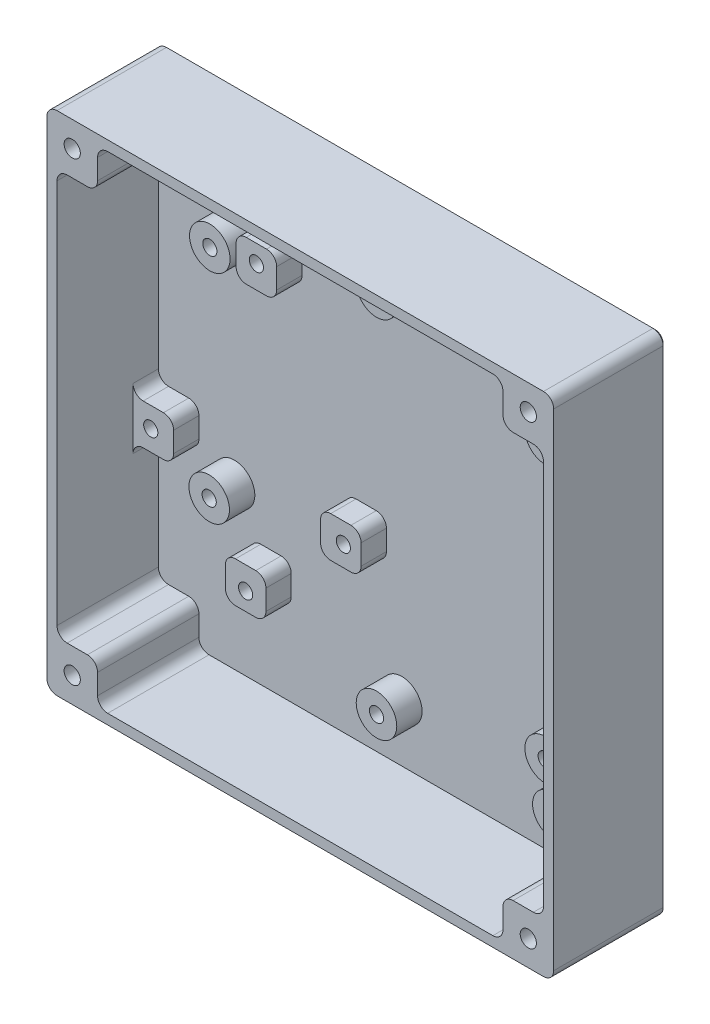
SolidWorks part; units mm, degrees
ref_plane "前视基准面" through (0, 0, 0) normal (0, 0, 1) x (1, 0, 0)
ref_plane "上视基准面" through (0, 0, 0) normal (0, 1, 0) x (1, 0, 0)
ref_plane "右视基准面" through (0, 0, 0) normal (1, 0, 0) x (0, 0, -1)
sketch "草图1" plane through (0, 0, 0) normal (0, 0, 1) x (1, 0, 0)
  line L1 (0, 0) -> (100, 0)
  line L2 (0, 0) -> (0, 100)
  line L3 (0, 100) -> (100, 100)
  line L4 (100, 0) -> (100, 100)
  dimension "D1" = 100
  dimension "D2" = 100
extrude "凸台-拉伸1" add sketch "草图1" along normal blind 2
sketch "草图2" plane through (0, 0, 2) normal (0, 0, 1) x (1, 0, 0)
  line L4 (98, 98) -> (2, 98)
  line L5 (2, 98) -> (2, 2)
  line L6 (2, 2) -> (98, 2)
  line L7 (98, 2) -> (98, 98)
  line L8 (0, 100) -> (0, 0)
  line L9 (0, 0) -> (100, 0)
  line L10 (100, 0) -> (100, 100)
  line L11 (100, 100) -> (0, 100)
  line L12 (0, 100) -> (0, 0)
  line L13 (0, 0) -> (100, 0)
  line L14 (100, 0) -> (100, 100)
  line L15 (100, 100) -> (0, 100)
  dimension "D1" = 0
  dimension "D2" = 2
extrude "凸台-拉伸2" add sketch "草图2" along normal blind 20
sketch "草图3" plane through (0, 0, 22) normal (0, 0, 1) x (1, 0, 0)
  line L0 (98, 98) -> (2, 98) construction
  line L1 (90, 98) -> (98, 98)
  line L2 (90, 98) -> (90, 90)
  line L3 (90, 90) -> (98, 90)
  line L4 (98, 98) -> (98, 90)
  line L5 (98, 2) -> (98, 98) construction
  line L7 (2, 98) -> (10, 98)
  line L8 (2, 98) -> (2, 90)
  line L9 (2, 90) -> (10, 90)
  line L10 (10, 98) -> (10, 90)
  line L11 (2, 2) -> (10, 2)
  line L12 (2, 2) -> (2, 10)
  line L13 (2, 10) -> (10, 10)
  line L14 (10, 2) -> (10, 10)
  line L15 (98, 2) -> (90, 2)
  line L16 (98, 2) -> (98, 10)
  line L17 (98, 10) -> (90, 10)
  line L18 (90, 2) -> (90, 10)
  dimension "D1" = 8
  dimension "D2" = 8
  dimension "D3" = 8
  dimension "D4" = 8
  dimension "D5" = 8
  dimension "D6" = 8
  dimension "D7" = 8
  dimension "D8" = 8
extrude "凸台-拉伸3" add sketch "草图3" against normal up to surface (20 mm away) up to face at (50, 50, 2)
sketch "草图4" plane through (0, 0, 22) normal (0, 0, 1) x (1, 0, 0)
  line L0 (100, 100) -> (0, 100) construction
  line L1 (0, 100) -> (0, 0) construction
  circle A0 centre (5, 95) radius 1.6
  circle A1 centre (95, 95) radius 1.6
  circle A2 centre (95, 5) radius 1.6
  circle A3 centre (5, 5) radius 1.6
  dimension "D1" = 3.2
  dimension "D2" = 5
  dimension "D3" = 5
  dimension "D4" = 2
  dimension "D5" = 2
extrude "切除-拉伸1" cut sketch "草图4" against normal through all
sketch "草图5" plane through (0, 0, 0) normal (0, 0, -1) x (-1, 0, 0)
  circle A0 centre (-95, 5) radius 3.05
  circle A1 centre (-5, 5) radius 3.05
  circle A2 centre (-5, 95) radius 3.05
  circle A3 centre (-95, 95) radius 3.05
  dimension "D1" = 6.1
  dimension "D2" = 2
  dimension "D3" = 2
extrude "切除-拉伸2" cut sketch "草图5" against normal blind 15
sketch "草图6" plane through (0, 0, 2) normal (0, 0, 1) x (1, 0, 0)
  circle A0 centre (50.0396, 85.2027) radius 4
  circle A1 centre (84.7107, 85.7107) radius 4
  circle A2 centre (84.8377, 13.4475) radius 4
  circle A3 centre (50.0396, 13.3205) radius 4
  dimension "D1" = 8
  dimension "D2" = 8
  dimension "D3" = 8
  dimension "D4" = 8
extrude "凸台-拉伸4" add sketch "草图6" along normal blind 5
sketch "草图7" plane through (0, 0, 7) normal (0, 0, 1) x (1, 0, 0)
  circle A0 centre (50.0396, 85.2027) radius 1.4
  circle A1 centre (84.7107, 85.7107) radius 1.4
  circle A2 centre (84.8377, 13.4475) radius 1.4
  circle A3 centre (50.0396, 13.3205) radius 1.4
  dimension "D1" = 2.8
  dimension "D2" = 2.8
  dimension "D3" = 2.8
  dimension "D4" = 2.8
extrude "切除-拉伸3" cut sketch "草图7" against normal blind 6
sketch "草图8" plane through (0, 0, 2) normal (0, 0, 1) x (1, 0, 0)
  circle A0 centre (17.1546, 76.6947) radius 4
  circle A1 centre (83.3217, 76.6947) radius 4
  circle A2 centre (83.3217, 22.2116) radius 4
  circle A3 centre (17.0276, 33.7686) radius 4
  dimension "D1" = 8
  dimension "D2" = 8
  dimension "D3" = 8
  dimension "D4" = 8
extrude "凸台-拉伸5" add sketch "草图8" along normal blind 5
sketch "草图9" plane through (0, 0, 7) normal (0, 0, 1) x (1, 0, 0)
  circle A0 centre (17.1546, 76.6947) radius 1.4
  circle A1 centre (83.3217, 76.6947) radius 1.4
  circle A2 centre (83.3217, 22.2116) radius 1.4
  circle A3 centre (17.0276, 33.7686) radius 1.4
  dimension "D1" = 2.8
  dimension "D2" = 2.8
  dimension "D3" = 2.8
  dimension "D4" = 2.8
extrude "切除-拉伸4" cut sketch "草图9" against normal blind 6
sketch "草图10" plane through (0, 0, 2) normal (0, 0, 1) x (1, 0, 0)
  line L0 (7, 77) -> (42, 77) construction
  line L1 (22.3409, 82) -> (30.3409, 82)
  line L2 (22.3409, 82) -> (22.3409, 74)
  line L3 (22.3409, 74) -> (30.3409, 74)
  line L4 (30.3409, 82) -> (30.3409, 74)
  line L5 (39, 43.1287) -> (47, 43.1287)
  line L6 (39, 43.1287) -> (39, 35.1287)
  line L7 (39, 35.1287) -> (47, 35.1287)
  line L8 (47, 43.1287) -> (47, 35.1287)
  line L9 (20.2165, 26) -> (28.2165, 26)
  line L10 (20.2165, 26) -> (20.2165, 18)
  line L11 (20.2165, 18) -> (28.2165, 18)
  line L12 (28.2165, 26) -> (28.2165, 18)
  line L13 (10, 43.8717) -> (2, 43.8717)
  line L14 (10, 43.8717) -> (10, 35.8717)
  line L15 (10, 35.8717) -> (2, 35.8717)
  line L16 (2, 43.8717) -> (2, 35.8717)
  line L17 (7, 23) -> (7, 46.8587) construction
  line L18 (7, 23) -> (42, 23) construction
  line L19 (42, 23) -> (42, 47.0044) construction
  dimension "D1" = 8
  dimension "D2" = 8
  dimension "D3" = 3
  dimension "D4" = 8
  dimension "D5" = 8
  dimension "D6" = 3
  dimension "D7" = 8
  dimension "D8" = 8
  dimension "D9" = 3
  dimension "D10" = 8
  dimension "D11" = 8
  dimension "D12" = 3
extrude "凸台-拉伸6" add sketch "草图10" along normal blind 5
sketch "草图11" plane through (0, 0, 7) normal (0, 0, 1) x (1, 0, 0)
  line L0 (7, 23) -> (7, 46.8587) construction
  line L1 (42, 23) -> (42, 47.0044) construction
  line L2 (7, 23) -> (42, 23) construction
  line L3 (7, 77) -> (42, 77) construction
  circle A0 centre (26.3409, 78.5) radius 1.4
  circle A1 centre (43.5, 39.1287) radius 1.4
  circle A2 centre (5.5, 39.8717) radius 1.4
  circle A3 centre (24.2165, 21.5) radius 1.4
  dimension "D1" = 2.8
  dimension "D2" = 1.5
  dimension "D3" = 2.8
  dimension "D4" = 1.5
  dimension "D5" = 2.8
  dimension "D6" = 1.5
  dimension "D7" = 2.8
  dimension "D8" = 1.5
extrude "切除-拉伸5" cut sketch "草图11" against normal blind 5
fillet "圆角1" radius 2 4 edges at (100, 100, 11) (100, 0, 11) (0, 100, 11) (0, 0, 11)
fillet "圆角2" radius 2 28 edges at (22.3409, 74, 4.5) (30.3409, 74, 4.5) (30.3409, 82, 4.5) (22.3409, 82, 4.5) (20.2165, 18, 4.5) (28.2165, 18, 4.5) (28.2165, 26, 4.5) (20.2165, 26, 4.5) (39, 35.1287, 4.5) (47, 43.1287, 4.5) (39, 43.1287, 4.5) (47, 35.1287, 4.5) (2, 43.8717, 4.5) (2, 90, 12) (10, 98, 12) (90, 98, 12) (90, 90, 12) (98, 90, 12) (98, 10, 12) (90, 10, 12) (90, 2, 12) (10, 2, 12) (10, 10, 12) (2, 10, 12) (2, 35.8717, 4.5) (10, 35.8717, 4.5) (10, 43.8717, 4.5) (10, 90, 12)
chamfer "倒角1" distance 0.4 angle 45 12 edges at (0.5858, 99.4142, 0) (0, 50, 0) (0.5858, 0.5858, 0) (50, 0, 0) (99.4142, 0.5858, 0) (100, 50, 0) (99.4142, 99.4142, 0) (50, 100, 0) (91.95, 5, 0) (1.95, 5, 0) (1.95, 95, 0) (91.95, 95, 0)
